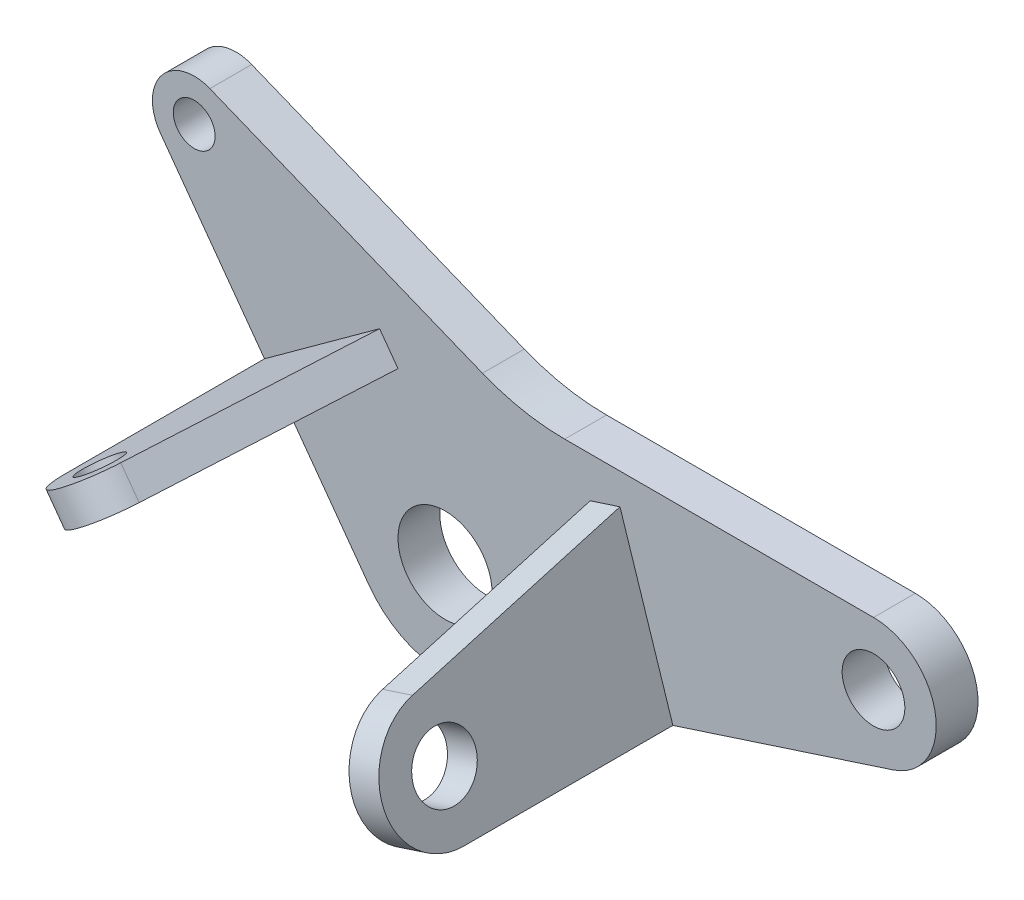
SolidWorks part; units mm, degrees
ref_plane "Front Plane" through (0, 0, 0) normal (0, 0, 1) x (1, 0, 0)
ref_plane "Top Plane" through (0, 0, 0) normal (0, 1, 0) x (1, 0, 0)
ref_plane "Right Plane" through (0, 0, 0) normal (1, 0, 0) x (0, 0, -1)
sketch "Sketch1" plane through (0, 0, 0) normal (0, 0, 1) x (1, 0, 0)
  line L0 (22.8999, 32.3346) -> (82, 32.3346)
  line L1 (5.5623, -17.119) -> (85.7082, 8.922)
  line L2 (-14.5623, -10.5801) -> (-54.4721, 44.351)
  line L3 (7.1664, 35.3929) -> (-45.0031, 56.4708)
  line L6 (37.8982, -6.6124) -> (22.7743, 39.9341) construction
  line L9 (-34.547, 16.9264) -> (3.6981, 44.7131) construction
  circle A0 centre (0, 0) radius 9
  arc A1 (-14.5623, -10.5801) -> (5.5623, -17.119) centre (0, 0) ccw
  arc A2 (7.1664, 35.3929) -> (22.8999, 32.3346) centre (22.8999, 74.3346) ccw
  circle A3 centre (82, 20.3346) radius 6
  arc A4 (85.7082, 8.922) -> (82, 32.3346) centre (82, 20.3346) ccw
  circle A5 centre (-48, 49.0533) radius 4
  arc A6 (-45.0031, 56.4708) -> (-54.4721, 44.351) centre (-48, 49.0533) ccw
  point P3 (0, 0)
  point P12 (22.8999, 39.8622)
  point P20 (3.9612, 44.351)
  point P21 (0, 0)
  point P22 (0, 0)
  dimension "D1" = 82
  dimension "D2" = 18
  dimension "D3" = 36
  dimension "D4" = 12
  dimension "D5" = 24
  dimension "D6" = 42
  dimension "D8" = 48
  dimension "D9" = 16
  dimension "D10" = 8
  dimension "D7" = 18
  dimension "D11" = 54
  dimension "D12" = 22
  dimension "D15" = 34
  dimension "D16" = 34
extrude "Boss-Extrude1" add sketch "Sketch1" along normal blind 8
ref_plane "Plane1" through (32.3359, 10.5066, 0) normal (0.9511, 0.309, 0) x (-0.309, 0.9511, 0)
ref_plane "Plane2" through (-19.9847, 27.5066, 0) normal (0.5878, -0.809, 0) x (0.809, 0.5878, 0)
sketch "Sketch3" plane through (32.3359, 10.5066, 0) normal (0.9511, 0.309, 0) x (-0.309, 0.9511, 0)
  line L0 (-18, 8) -> (-18, 48)
  line L1 (5.7378, 50.4949) -> (14.7703, 8)
  line L2 (31.4461, 8) -> (67.6136, 8) construction
  line L3 (26.7736, 0) -> (41.3819, 0) construction
  line L4 (-18, 8) -> (-18, 0) construction
  line L5 (5.4127, 8) -> (-18, 8) construction
  line L6 (23.6756, 8) -> (5.4127, 8) construction
  line L7 (14.7703, 8) -> (-18, 8)
  arc A0 (5.7378, 50.4949) -> (-18, 48) centre (-6, 48) ccw
  circle A1 centre (-6, 48) radius 6
  dimension "D1" = 78
  dimension "D2" = 24
  dimension "D3" = 12
  dimension "D4" = 48
sketch "Sketch4" plane through (-19.9847, 27.5066, 0) normal (0.5878, -0.809, 0) x (0.809, 0.5878, 0)
  line L0 (-18, 8) -> (-18, 46)
  line L1 (-2.3099, 48.2051) -> (9.2187, 8)
  line L2 (-18, 0) -> (29.2735, 0) construction
  line L3 (-5.5623, 8) -> (-18, 8) construction
  line L4 (-18, 8) -> (-18, 0) construction
  line L6 (-5.5623, 8) -> (74.5836, 8) construction
  line L7 (9.2187, 8) -> (-18, 8)
  circle A0 centre (-10, 46) radius 4
  arc A1 (-2.3099, 48.2051) -> (-18, 46) centre (-10, 46) ccw
  dimension "D1" = 46
  dimension "D3" = 16
  dimension "D4" = 8
  dimension "D2" = 74
extrude "Boss-Extrude3" add sketch "Sketch4" along normal blind 6 contours L1 A1 L0 L7 A0
extrude "Boss-Extrude4" add sketch "Sketch3" along normal blind 6
